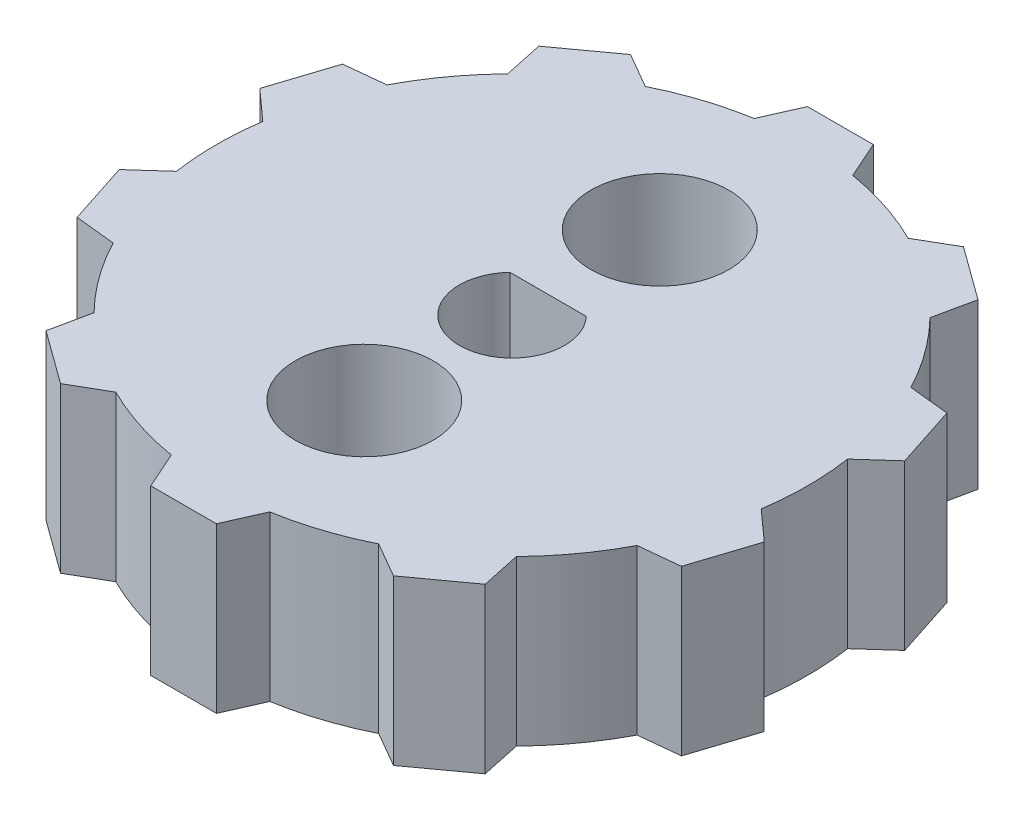
SolidWorks part; units mm, degrees
ref_plane "前视基准面" through (0, 0, 0) normal (0, 0, 1) x (1, 0, 0)
ref_plane "上视基准面" through (0, 0, 0) normal (0, 1, 0) x (1, 0, 0)
ref_plane "右视基准面" through (0, 0, 0) normal (1, 0, 0) x (0, 0, -1)
sketch "草图1" plane through (0, 0, 0) normal (0, 1, 0) x (1, 0, 0)
  line L0 (-1.1619, 1.1) -> (1.1619, 1.1)
  circle A0 centre (0, 0) radius 9
  circle A1 centre (0, 0) radius 1.6
  dimension "D1" = 3.2
  dimension "D2" = 1.1
  dimension "D3" = 18
extrude "凸台-拉伸1" add sketch "草图1" along normal blind 5 contours A0 A1 | L0 A1
sketch "草图2" plane through (0, 5, 0) normal (0, 1, 0) x (1, 0, 0)
  line L0 (0, 0) -> (0, 9) construction
  line L1 (0, 9) -> (0, 6.2976) construction
  line L2 (1, 10) -> (-1, 10)
  line L3 (-1, 10) -> (-1.5, 8.8741)
  line L4 (1, 10) -> (1.5, 8.8741)
  circle A0 centre (0, 0) radius 9 construction
  circle A2 centre (0, 0) radius 9
  circle A3 centre (0, 0) radius 9
  point P12 (0, 10)
  circle M7 centre (0, 0) radius 9
  dimension "D2" = 1
  dimension "D3" = 1.5
  dimension "D4" = 1
  dimension "D1" = 0
extrude "凸台-拉伸2" add sketch "草图2" against normal up to surface (5 mm away) contours L4 L2 L3 M7 up to face at (0, 0, 0.25)
pattern_circular "阵列(圆周)1" count 10 over 360 about axis through (0, 0, 0) along (0, 1, 0) of "凸台-拉伸2"
sketch "草图3" plane through (0, 5, 0) normal (0, 1, 0) x (1, 0, 0)
  circle A0 centre (0, 4.5) radius 2.1
  circle A1 centre (0, -4.5) radius 2.1
  dimension "D1" = 4.2
  dimension "D2" = 9
  dimension "D3" = 4.5
extrude "切除-拉伸1" cut sketch "草图3" against normal up to next
